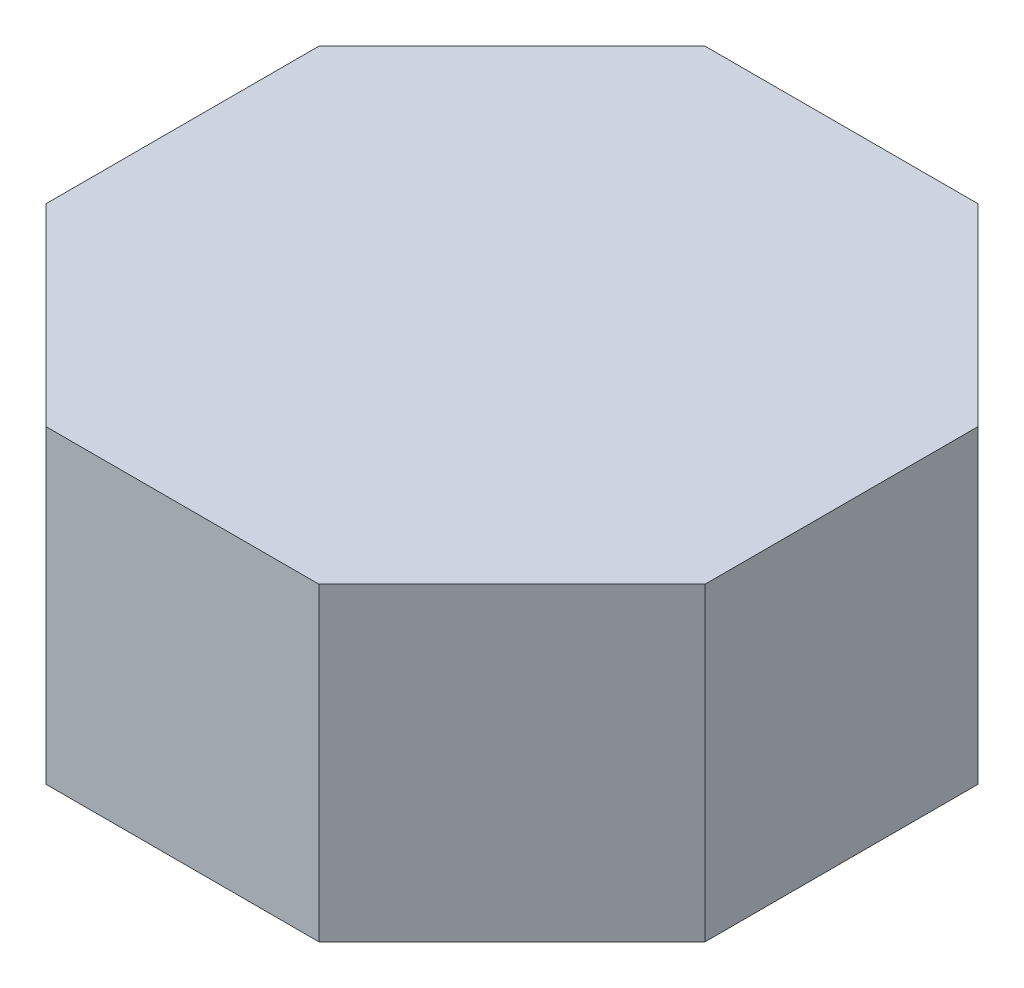
SolidWorks part; units mm, degrees
ref_plane "Front Plane" through (0, 0, 0) normal (0, 0, 1) x (1, 0, 0)
ref_plane "Top Plane" through (0, 0, 0) normal (0, 1, 0) x (1, 0, 0)
ref_plane "Right Plane" through (0, 0, 0) normal (1, 0, 0) x (0, 0, -1)
sketch "Sketch1" plane through (0, 0, 0) normal (0, 1, 0) x (1, 0, 0)
  line L0 (-2, 0.8284) -> (-0.8284, 2)
  line L1 (-0.8284, 2) -> (0.8284, 2)
  line L2 (0.8284, 2) -> (2, 0.8284)
  line L3 (2, 0.8284) -> (2, -0.8284)
  line L4 (2, -0.8284) -> (0.8284, -2)
  line L5 (0.8284, -2) -> (-0.8284, -2)
  line L6 (-0.8284, -2) -> (-2, -0.8284)
  line L7 (-2, -0.8284) -> (-2, 0.8284)
  line L8 (-2, 0) -> (2, 0) construction
  dimension "D1" = 4
  dimension "D2" = 4
extrude "Extrude1" add sketch "Sketch1" along normal blind 1.88
